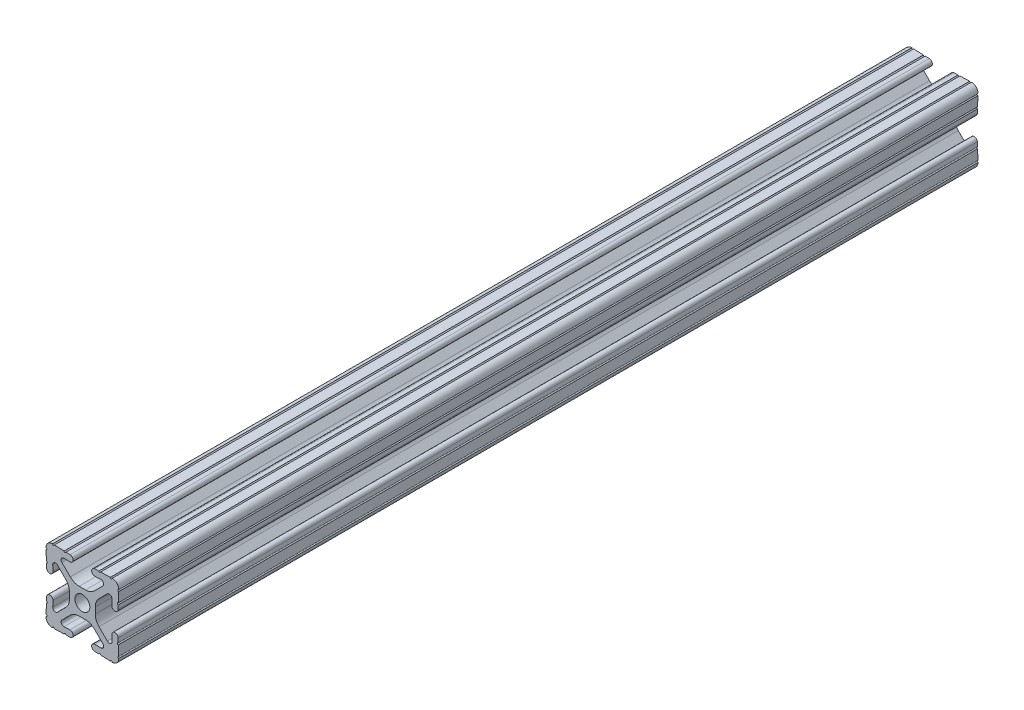
SolidWorks part; units mm, degrees
ref_plane "Front Plane" through (0, 0, 0) normal (0, 0, 1) x (1, 0, 0)
ref_plane "Top Plane" through (0, 0, 0) normal (0, 1, 0) x (1, 0, 0)
ref_plane "Right Plane" through (0, 0, 0) normal (1, 0, 0) x (0, 0, -1)
sketch "Sketch1" plane through (0, 0, 0) normal (0, 0, 1) x (1, 0, 0)
  line L0 (0, 12.7) -> (-12.7814, 12.7) construction
  line L1 (-4.5085, 0) -> (-4.5085, 2.9459)
  line L2 (-6.0437, 12.5461) -> (-10.0976, 12.6876) construction
  line L3 (-11.5616, 12.4229) -> (-4.3159, 12.1699) construction
  line L4 (-6.4364, 10.3486) -> (-6.3592, 12.5571) construction
  line L6 (-2.9459, 4.5085) -> (0, 4.5085)
  line L7 (0, 0) -> (0, 12.7) construction
  line L8 (0, 0) -> (-12.7814, 0) construction
  line L9 (0.7813, 0.7813) -> (-0.7813, -0.7813) construction
  line L10 (-2.9459, 4.5085) -> (-7.1484, 8.711)
  line L11 (-4.5085, 2.9459) -> (-8.711, 7.1484)
  line L13 (0, 0) -> (-12.7814, 12.7814) construction
  line L14 (-10.4131, 12.6987) -> (-4.3048, 12.4853)
  line L15 (-4.3048, 12.4853) -> (-4.382, 10.2769) construction
  line L16 (-4.382, 10.2769) -> (-6.4364, 10.3486)
  line L17 (-12.6987, 10.4131) -> (-12.4853, 4.3048)
  line L18 (-10.2769, 4.382) -> (-10.3486, 6.4364)
  circle A0 centre (0, 0) radius 2.6035
  arc A1 (-4.382, 10.2769) -> (-4.3048, 12.4853) centre (-4.3434, 11.3811) ccw
  arc A2 (-7.1484, 8.711) -> (-6.4364, 10.3486) centre (-6.4698, 9.3896) cw
  arc A3 (-8.711, 7.1484) -> (-10.3486, 6.4364) centre (-9.3896, 6.4698) ccw
  arc A4 (-10.2769, 4.382) -> (-12.4853, 4.3048) centre (-11.3811, 4.3434) cw
  arc A5 (-10.4131, 12.6987) -> (-12.6987, 10.4131) centre (-10.4902, 10.4902) ccw
  arc A6 (-10.4131, 12.6987) -> (-9.7821, 12.6766) centre (-10.0976, 12.6876) ccw
  arc A7 (-6.3592, 12.5571) -> (-5.7282, 12.5351) centre (-6.0437, 12.5461) ccw
  arc A8 (-12.5571, 6.3592) -> (-12.5351, 5.7282) centre (-12.5461, 6.0437) cw
  arc A9 (-12.6987, 10.4131) -> (-12.6766, 9.7821) centre (-12.6876, 10.0976) cw
  dimension "D1" = 5.207
  dimension "D5" = 14.859
  dimension "D9" = 2
  dimension "D2" = 25.4
  dimension "D12" = 0.6314
  dimension "D10" = 2.2098
  dimension "D3" = 9.017
  dimension "D4" = 9.017
  dimension "D6" = 25.4
  dimension "D7" = 6.477
  dimension "D8" = 2.2098
  dimension "D11" = 12.7
sketch "Sketch3" plane through (0, 0, 0) normal (0, 0, 1) x (1, 0, 0)
  line L0 (-2.9459, 4.5085) -> (0, 4.5085) construction
  line L1 (-2.9459, 4.5085) -> (-7.1484, 8.711) construction
  line L2 (-4.382, 10.2769) -> (-6.4364, 10.3486) construction
  line L3 (-10.4131, 12.6987) -> (-4.3048, 12.4853) construction
  line L4 (-4.5085, 0) -> (-4.5085, 2.9459) construction
  line L5 (-4.5085, 2.9459) -> (-8.711, 7.1484) construction
  line L6 (-10.2769, 4.382) -> (-10.3486, 6.4364) construction
  line L7 (-12.6987, 10.4131) -> (-12.4853, 4.3048) construction
  line L8 (-1.1153, 4.5085) -> (1.1153, 4.5085)
  line L9 (-4.2404, 5.803) -> (-7.1484, 8.711)
  line L10 (-4.382, 10.2769) -> (-6.4364, 10.3486)
  line L11 (-9.7821, 12.6766) -> (-6.3592, 12.5571)
  line L12 (-4.5085, -1.1153) -> (-4.5085, 1.1153)
  line L13 (-5.803, 4.2404) -> (-8.711, 7.1484)
  line L14 (-10.2769, 4.382) -> (-10.3486, 6.4364)
  line L15 (-12.6766, 9.7821) -> (-12.5571, 6.3592)
  line L16 (-5.7282, 12.5351) -> (-4.3048, 12.4853)
  line L17 (-12.5351, 5.7282) -> (-12.4853, 4.3048)
  line L18 (0, 0) -> (0, 12.7) construction
  line L19 (0, 0) -> (-12.7814, 0) construction
  line L20 (12.5351, 5.7282) -> (12.4853, 4.3048)
  line L21 (5.7282, 12.5351) -> (4.3048, 12.4853)
  line L22 (12.6766, 9.7821) -> (12.5571, 6.3592)
  line L23 (10.2769, 4.382) -> (10.3486, 6.4364)
  line L24 (5.803, 4.2404) -> (8.711, 7.1484)
  line L25 (4.5085, -1.1153) -> (4.5085, 1.1153)
  line L26 (9.7821, 12.6766) -> (6.3592, 12.5571)
  line L27 (4.382, 10.2769) -> (6.4364, 10.3486)
  line L28 (4.2404, 5.803) -> (7.1484, 8.711)
  line L29 (4.2404, -5.803) -> (7.1484, -8.711)
  line L30 (4.382, -10.2769) -> (6.4364, -10.3486)
  line L31 (9.7821, -12.6766) -> (6.3592, -12.5571)
  line L32 (5.803, -4.2404) -> (8.711, -7.1484)
  line L33 (10.2769, -4.382) -> (10.3486, -6.4364)
  line L34 (12.6766, -9.7821) -> (12.5571, -6.3592)
  line L35 (5.7282, -12.5351) -> (4.3048, -12.4853)
  line L36 (12.5351, -5.7282) -> (12.4853, -4.3048)
  line L37 (-12.5351, -5.7282) -> (-12.4853, -4.3048)
  line L38 (-5.7282, -12.5351) -> (-4.3048, -12.4853)
  line L39 (-12.6766, -9.7821) -> (-12.5571, -6.3592)
  line L40 (-10.2769, -4.382) -> (-10.3486, -6.4364)
  line L41 (-5.803, -4.2404) -> (-8.711, -7.1484)
  line L42 (-9.7821, -12.6766) -> (-6.3592, -12.5571)
  line L43 (-4.382, -10.2769) -> (-6.4364, -10.3486)
  line L44 (-4.2404, -5.803) -> (-7.1484, -8.711)
  line L45 (-1.1153, -4.5085) -> (1.1153, -4.5085)
  arc A0 (-10.4131, 12.6987) -> (-9.7821, 12.6766) centre (-10.0976, 12.6876) ccw construction
  arc A1 (-6.4364, 10.3486) -> (-7.1484, 8.711) centre (-6.4698, 9.3896) ccw construction
  arc A2 (-4.382, 10.2769) -> (-4.3048, 12.4853) centre (-4.3434, 11.3811) ccw construction
  arc A3 (-8.711, 7.1484) -> (-10.3486, 6.4364) centre (-9.3896, 6.4698) ccw construction
  arc A4 (-12.4853, 4.3048) -> (-10.2769, 4.382) centre (-11.3811, 4.3434) ccw construction
  arc A5 (-6.3592, 12.5571) -> (-5.7282, 12.5351) centre (-6.0437, 12.5461) ccw construction
  arc A6 (-10.4131, 12.6987) -> (-12.6987, 10.4131) centre (-10.4902, 10.4902) ccw construction
  arc A7 (-12.6766, 9.7821) -> (-12.6987, 10.4131) centre (-12.6876, 10.0976) ccw construction
  arc A8 (-12.5351, 5.7282) -> (-12.5571, 6.3592) centre (-12.5461, 6.0437) ccw construction
  arc A9 (-10.4131, 12.6987) -> (-9.7821, 12.6766) centre (-10.0976, 12.6876) ccw
  arc A10 (-6.4364, 10.3486) -> (-7.1484, 8.711) centre (-6.4698, 9.3896) ccw
  arc A11 (-4.382, 10.2769) -> (-4.3048, 12.4853) centre (-4.3434, 11.3811) ccw
  arc A12 (-8.711, 7.1484) -> (-10.3486, 6.4364) centre (-9.3896, 6.4698) ccw
  arc A13 (-12.4853, 4.3048) -> (-10.2769, 4.382) centre (-11.3811, 4.3434) ccw
  arc A14 (-6.3592, 12.5571) -> (-5.7282, 12.5351) centre (-6.0437, 12.5461) ccw
  arc A15 (-10.4131, 12.6987) -> (-12.6987, 10.4131) centre (-10.4902, 10.4902) ccw
  arc A16 (-12.6766, 9.7821) -> (-12.6987, 10.4131) centre (-12.6876, 10.0976) ccw
  arc A17 (-12.5351, 5.7282) -> (-12.5571, 6.3592) centre (-12.5461, 6.0437) ccw
  arc A18 (-1.1153, 4.5085) -> (-4.2404, 5.803) centre (-1.1153, 8.9281) cw
  arc A19 (4.5085, 1.1153) -> (5.803, 4.2404) centre (8.9281, 1.1153) cw
  arc A20 (1.1153, 4.5085) -> (4.2404, 5.803) centre (1.1153, 8.9281) ccw
  arc A21 (-4.5085, 1.1153) -> (-5.803, 4.2404) centre (-8.9281, 1.1153) ccw
  arc A22 (12.5351, 5.7282) -> (12.5571, 6.3592) centre (12.5461, 6.0437) cw
  arc A23 (12.6766, 9.7821) -> (12.6987, 10.4131) centre (12.6876, 10.0976) cw
  arc A24 (10.4131, 12.6987) -> (12.6987, 10.4131) centre (10.4902, 10.4902) cw
  arc A25 (6.3592, 12.5571) -> (5.7282, 12.5351) centre (6.0437, 12.5461) cw
  arc A26 (12.4853, 4.3048) -> (10.2769, 4.382) centre (11.3811, 4.3434) cw
  arc A27 (8.711, 7.1484) -> (10.3486, 6.4364) centre (9.3896, 6.4698) cw
  arc A28 (4.382, 10.2769) -> (4.3048, 12.4853) centre (4.3434, 11.3811) cw
  arc A29 (6.4364, 10.3486) -> (7.1484, 8.711) centre (6.4698, 9.3896) cw
  arc A30 (10.4131, 12.6987) -> (9.7821, 12.6766) centre (10.0976, 12.6876) cw
  arc A31 (10.4131, -12.6987) -> (9.7821, -12.6766) centre (10.0976, -12.6876) ccw
  arc A32 (6.4364, -10.3486) -> (7.1484, -8.711) centre (6.4698, -9.3896) ccw
  arc A33 (4.382, -10.2769) -> (4.3048, -12.4853) centre (4.3434, -11.3811) ccw
  arc A34 (8.711, -7.1484) -> (10.3486, -6.4364) centre (9.3896, -6.4698) ccw
  arc A35 (12.4853, -4.3048) -> (10.2769, -4.382) centre (11.3811, -4.3434) ccw
  arc A36 (6.3592, -12.5571) -> (5.7282, -12.5351) centre (6.0437, -12.5461) ccw
  arc A37 (10.4131, -12.6987) -> (12.6987, -10.4131) centre (10.4902, -10.4902) ccw
  arc A38 (12.6766, -9.7821) -> (12.6987, -10.4131) centre (12.6876, -10.0976) ccw
  arc A39 (12.5351, -5.7282) -> (12.5571, -6.3592) centre (12.5461, -6.0437) ccw
  arc A40 (-4.5085, -1.1153) -> (-5.803, -4.2404) centre (-8.9281, -1.1153) cw
  arc A41 (1.1153, -4.5085) -> (4.2404, -5.803) centre (1.1153, -8.9281) cw
  arc A42 (4.5085, -1.1153) -> (5.803, -4.2404) centre (8.9281, -1.1153) ccw
  arc A43 (-1.1153, -4.5085) -> (-4.2404, -5.803) centre (-1.1153, -8.9281) ccw
  arc A44 (-12.5351, -5.7282) -> (-12.5571, -6.3592) centre (-12.5461, -6.0437) cw
  arc A45 (-12.6766, -9.7821) -> (-12.6987, -10.4131) centre (-12.6876, -10.0976) cw
  arc A46 (-10.4131, -12.6987) -> (-12.6987, -10.4131) centre (-10.4902, -10.4902) cw
  arc A47 (-6.3592, -12.5571) -> (-5.7282, -12.5351) centre (-6.0437, -12.5461) cw
  arc A48 (-12.4853, -4.3048) -> (-10.2769, -4.382) centre (-11.3811, -4.3434) cw
  arc A49 (-8.711, -7.1484) -> (-10.3486, -6.4364) centre (-9.3896, -6.4698) cw
  arc A50 (-4.382, -10.2769) -> (-4.3048, -12.4853) centre (-4.3434, -11.3811) cw
  arc A51 (-6.4364, -10.3486) -> (-7.1484, -8.711) centre (-6.4698, -9.3896) cw
  arc A52 (-10.4131, -12.6987) -> (-9.7821, -12.6766) centre (-10.0976, -12.6876) cw
  circle A53 centre (0, 0) radius 2.6035 construction
  circle A54 centre (0, 0) radius 2.6035
  point P135 (4.5085, 0)
  dimension "D2" = 4.4196
extrude "Extrude1" add sketch "Sketch3" along normal mid plane 300
equation "\"D10@Sketch1\" = \"D8@Sketch1\""
equation "\"D11@Sketch1\" = \"D6@Sketch1\"/2"
equation "\"D12@Sketch1\" = \"D8@Sketch1\"/3.5"
equation "\"D2@Sketch3\" = \"D8@Sketch1\"*2"
